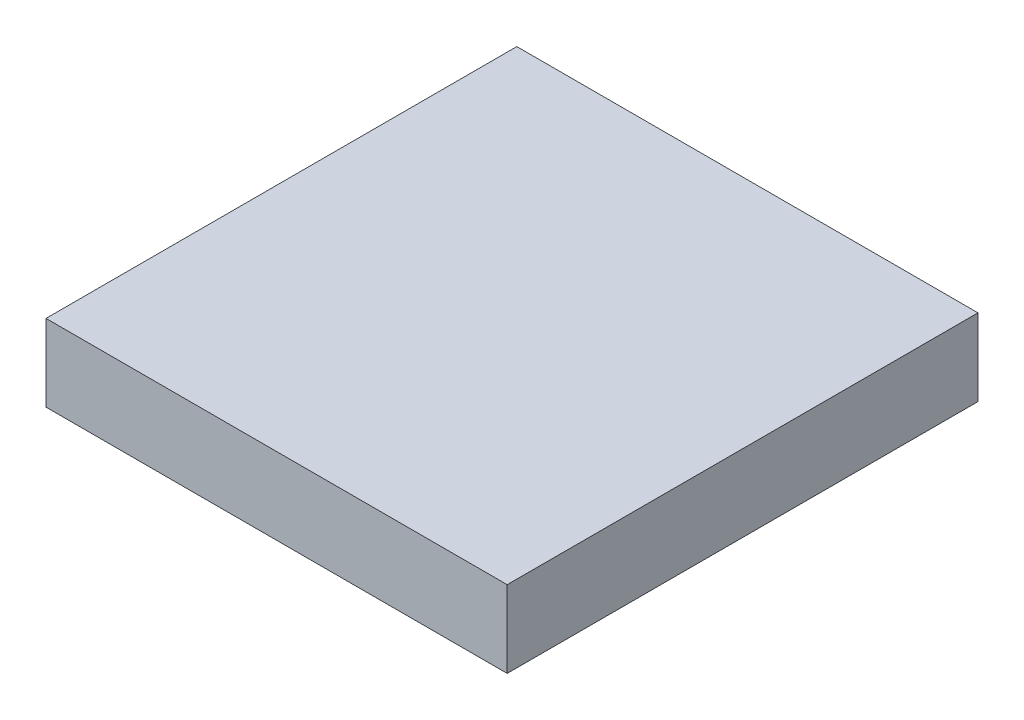
SolidWorks part; units mm, degrees
ref_plane "前视基准面" through (0, 0, 0) normal (0, 0, 1) x (1, 0, 0)
ref_plane "上视基准面" through (0, 0, 0) normal (0, 1, 0) x (1, 0, 0)
ref_plane "右视基准面" through (0, 0, 0) normal (1, 0, 0) x (0, 0, -1)
sketch "草图1" plane through (0, 0, 0) normal (0, 1, 0) x (1, 0, 0)
  line L1 (0, 0) -> (120, 0)
  line L2 (0, 0) -> (0, 122.5)
  line L3 (0, 122.5) -> (120, 122.5)
  line L4 (120, 0) -> (120, 122.5)
  dimension "D1" = 120
  dimension "D2" = 122.5
extrude "凸台-拉伸1" add sketch "草图1" along normal blind 20
sketch "草图2" plane through (0, 0, 0) normal (0, -1, 0) x (1, 0, 0)
  line L8 (1, -1) -> (1, -121.5)
  line L9 (1, -121.5) -> (119, -121.5)
  line L10 (119, -121.5) -> (119, -1)
  line L11 (119, -1) -> (1, -1)
  line L12 (1, -1) -> (1, -121.5)
  line L13 (1, -121.5) -> (119, -121.5)
  line L14 (119, -121.5) -> (119, -1)
  line L15 (119, -1) -> (1, -1)
  dimension "D1" = 1
extrude "切除-拉伸1" cut sketch "草图2" against normal offset from surface (19 mm away) 1 up to face at (60, 20, -61.25)
